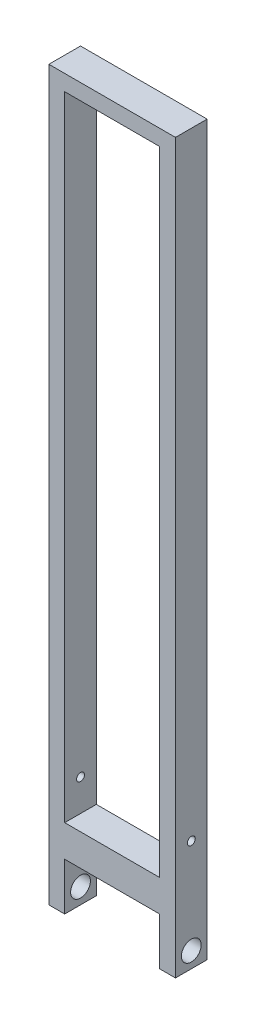
SolidWorks part; units mm, degrees
ref_plane "Front Plane" through (0, 0, 0) normal (0, 0, 1) x (1, 0, 0)
ref_plane "Top Plane" through (0, 0, 0) normal (0, 1, 0) x (1, 0, 0)
ref_plane "Right Plane" through (0, 0, 0) normal (1, 0, 0) x (0, 0, -1)
sketch "Sketch1" plane through (0, 0, 0) normal (0, 0, 1) x (1, 0, 0)
  line L0 (76.2, 25.4) -> (76.2, 1041.4)
  line L1 (-76.2, 25.4) -> (76.2, 25.4)
  line L3 (-76.2, -25.4) -> (76.2, -25.4)
  line L4 (-76.2, -25.4) -> (-76.2, -101.6)
  line L5 (-76.2, 25.4) -> (76.2, -25.4) construction
  line L6 (-76.2, -25.4) -> (76.2, 25.4) construction
  line L7 (76.2, -101.6) -> (101.6, -101.6)
  line L8 (76.2, -101.6) -> (76.2, -25.4)
  line L10 (101.6, -101.6) -> (101.6, 1066.8)
  line L11 (101.6, 1066.8) -> (-101.6, 1066.8)
  line L13 (76.2, 1041.4) -> (-76.2, 1041.4)
  line L16 (-76.2, 1041.4) -> (-76.2, 25.4)
  line L17 (-76.2, -101.6) -> (-101.6, -101.6)
  line L18 (-101.6, 1066.8) -> (-101.6, -101.6)
  point P0 (0, 0)
  dimension "D1" = 25.4
  dimension "D2" = 203.2
  dimension "D3" = 76.2
  dimension "D4" = 50.8
  dimension "D5" = 25.4
  dimension "D6" = 1168.4
extrude "Boss-Extrude1" add sketch "Sketch1" along normal blind 50.8
sketch "Sketch2" plane through (101.6, 0, 0) normal (1, 0, 0) x (0, 0, -1)
  line L0 (-25.4, -101.6) -> (-25.4, -76.2) construction
  line L1 (-50.8, -101.6) -> (0, -101.6) construction
  line L2 (-25.4, -76.2) -> (-50.8, -76.2) construction
  line L3 (-50.8, -101.6) -> (-50.8, 1066.8) construction
  circle A0 centre (-25.4, -76.2) radius 15.875
  circle A1 centre (-25.4, 76.2) radius 6.35
  point P5 (-25.4, -101.6)
  dimension "D1" = 31.75
  dimension "D3" = 12.7
  dimension "D2" = 152.4
extrude "Cut-Extrude1" cut sketch "Sketch2" against normal through all
